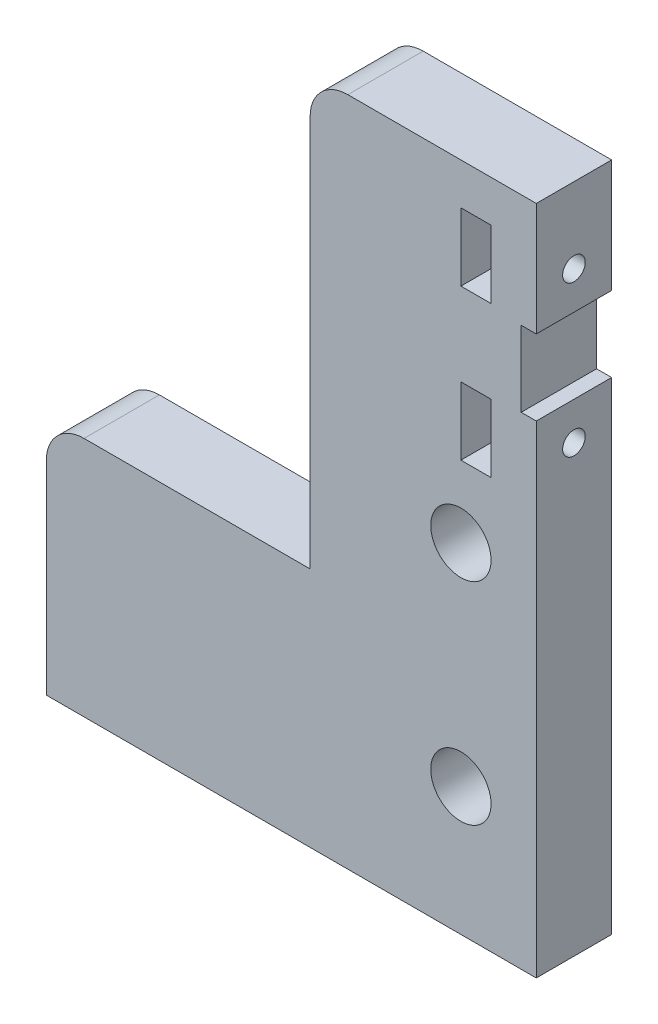
SolidWorks part; units mm, degrees
ref_plane "Front Plane" through (0, 0, 0) normal (0, 0, 1) x (1, 0, 0)
ref_plane "Top Plane" through (0, 0, 0) normal (0, 1, 0) x (1, 0, 0)
ref_plane "Right Plane" through (0, 0, 0) normal (1, 0, 0) x (0, 0, -1)
sketch "Sketch1" plane through (0, 0, 0) normal (0, 0, 1) x (1, 0, 0)
  line L0 (0, 0) -> (30, 0)
  line L1 (30, 0) -> (30, -84)
  line L2 (30, -84) -> (-35, -84)
  line L3 (-35, -84) -> (-35, -52)
  line L4 (-35, -52) -> (0, -52)
  line L5 (0, -52) -> (0, 0)
  circle A0 centre (20, -39) radius 4
  circle A1 centre (20, -67) radius 4
  dimension "D2" = 8
  dimension "D6" = 8
  dimension "D1" = 30
  dimension "D3" = 10
  dimension "D4" = 39
  dimension "D5" = 28
  dimension "D7" = 17
  dimension "D8" = 55
  dimension "D9" = 15
extrude "Boss-Extrude1" add sketch "Sketch1" along normal blind 10
sketch "Sketch2" plane through (0, 0, 10) normal (0, 0, 1) x (1, 0, 0)
  line L0 (30, -84) -> (30, 0) construction
  line L1 (30, -10) -> (28, -10)
  line L2 (30, -10) -> (30, -20)
  line L3 (30, -20) -> (28, -20)
  line L4 (28, -10) -> (28, -20)
  dimension "D1" = 10
  dimension "D2" = 10
  dimension "D3" = 2
extrude "Cut-Extrude1" cut sketch "Sketch2" against normal blind 10
sketch "Sketch3" plane through (30, 0, 0) normal (1, 0, 0) x (0, 0, -1)
  circle A0 centre (-5, -5) radius 1.5
  circle A1 centre (-5, -25) radius 1.5
  dimension "D1" = 3
  dimension "D2" = 3
  dimension "D3" = 5
extrude "Cut-Extrude2" cut sketch "Sketch3" against normal blind 10
sketch "Sketch4" plane through (0, 0, 10) normal (0, 0, 1) x (1, 0, 0)
  line L0 (30, -10) -> (30, 0) construction
  line L1 (20, -0.5) -> (24, -0.5)
  line L2 (20, -0.5) -> (20, -9.5)
  line L3 (20, -9.5) -> (24, -9.5)
  line L4 (24, -0.5) -> (24, -9.5)
  line L5 (28, -20) -> (30, -20) construction
  line L6 (24, -20.5) -> (20, -20.5)
  line L7 (24, -20.5) -> (24, -29.5)
  line L8 (24, -29.5) -> (20, -29.5)
  line L9 (20, -20.5) -> (20, -29.5)
  point P4 (20, -5)
  point P7 (30, -5)
  point P8 (22, -0.5)
  point P16 (29, -20)
  dimension "D1" = 9
  dimension "D2" = 0
  dimension "D3" = 4
  dimension "D4" = 8
  dimension "D5" = 9
  dimension "D6" = 0.5
extrude "Cut-Extrude3" cut sketch "Sketch4" against normal blind 10
sketch "Sketch5" plane through (0, 0, 0) normal (0, 1, 0) x (1, 0, 0)
  line L1 (0, -10) -> (30, -10)
  line L2 (0, -10) -> (0, 0)
  line L3 (0, 0) -> (30, 0)
  line L4 (30, -10) -> (30, 0)
extrude "Boss-Extrude2" add sketch "Sketch5" along normal blind 5
sketch "Sketch6" plane through (-35, 0, 0) normal (-1, 0, 0) x (0, 0, 1)
  line L0 (0, -52) -> (0, -84) construction
  circle A0 centre (0, -68) radius 8
  dimension "D1" = 16
extrude "Cut-Extrude4" cut sketch "Sketch6" against normal blind 48
sketch "Sketch7" plane through (0, 5, 0) normal (0, 1, 0) x (1, 0, 0)
  line L0 (30, 0) -> (0, 0) construction
  circle A0 centre (7, 0) radius 6
  dimension "D1" = 12
  dimension "D2" = 7
extrude "Cut-Extrude5" cut sketch "Sketch7" against normal blind 65
sketch "Sketch8" plane through (0, -60, 0) normal (0, 1, 0) x (1, 0, 0)
  line L0 (1, 0) -> (13, 0) construction
  circle A0 centre (7, 0) radius 6
extrude "Cut-Extrude6" cut sketch "Sketch8" against normal blind 16
sketch "Sketch9" plane through (0, 5, 0) normal (0, 1, 0) x (1, 0, 0)
  line L0 (13, 0) -> (1, 0)
  circle A0 centre (7, 0) radius 6
  arc M2 (13, 0) -> (1, 0) centre (7, 0) cw
extrude "Boss-Extrude3" add sketch "Sketch9" against normal blind 15 contours L0 M2
sketch "Sketch10" plane through (0, 0, 0) normal (0, 0, -1) x (-1, 0, 0)
  line L0 (-13, -10) -> (-1, -10) construction
  circle A0 centre (-7, -10) radius 6
extrude "Cut-Extrude7" cut sketch "Sketch10" against normal blind 6
fillet "Fillet1" radius 5 1 edges at (-35, -52, 5)
fillet "Fillet2" radius 5 1 edges at (0, 5, 5)
